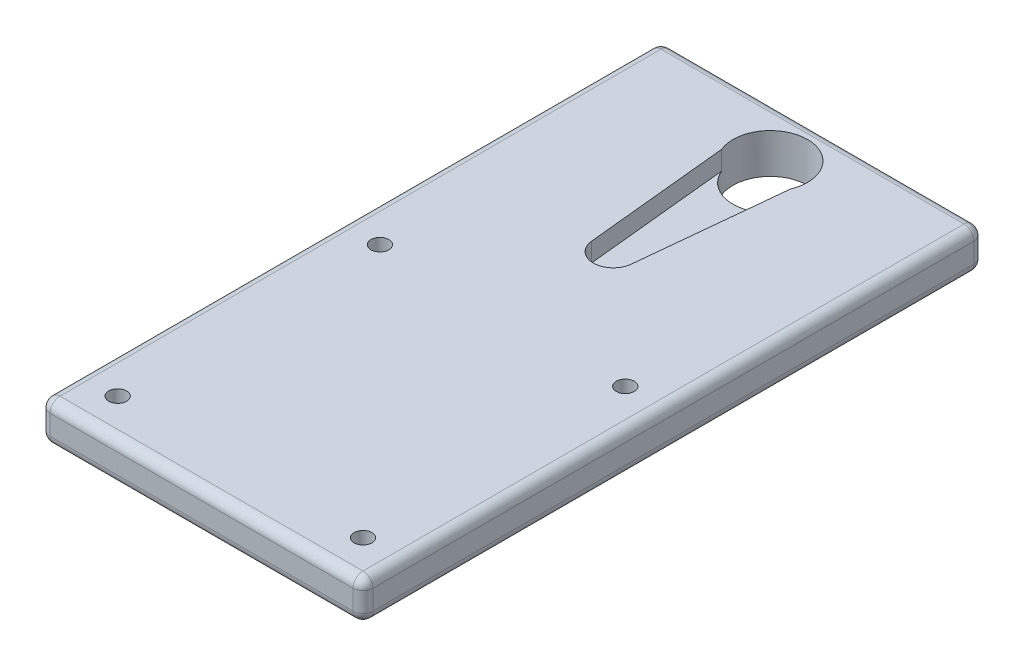
SolidWorks part; units mm, degrees
ref_plane "Front Plane" through (0, 0, 0) normal (0, 0, 1) x (1, 0, 0)
ref_plane "Top Plane" through (0, 0, 0) normal (0, 1, 0) x (1, 0, 0)
ref_plane "Right Plane" through (0, 0, 0) normal (1, 0, 0) x (0, 0, -1)
sketch "Sketch1" plane through (0, 0, 0) normal (0, 1, 0) x (1, 0, 0)
  line L1 (-16.25, 62.5) -> (16.25, 62.5)
  line L2 (-16.25, 62.5) -> (-16.25, 0)
  line L3 (-16.25, 0) -> (16.25, 0)
  line L4 (16.25, 62.5) -> (16.25, 0)
  point P4 (0, 0)
  dimension "D1" = 32.5
  dimension "D2" = 62.5
extrude "Base" add sketch "Sketch1" along normal blind 4
sketch "Sketch2" plane through (0, 4, 0) normal (0, 1, 0) x (1, 0, 0)
  line L0 (-3.4645, 55.8149) -> (-2, 41.25)
  line L1 (3.4645, 55.8149) -> (2, 41.25)
  line L2 (0, 62.5) -> (0, 0) construction
  line L3 (16.25, 62.5) -> (-16.25, 62.5) construction
  line L4 (-16.25, 0) -> (16.25, 0) construction
  arc A0 (-2, 41.25) -> (2, 41.25) centre (0, 41.4511) ccw
  arc A1 (-3.4645, 55.8149) -> (3.4645, 55.8149) centre (0, 57.25) cw
  point P11 (0, 39.441)
  point P13 (0, 61)
  point P14 (0, 0)
  dimension "D1" = 2.0101
  dimension "D4" = 3.75
  dimension "D2" = 14.5649
  dimension "D3" = 5.742
  dimension "D5" = 1.5
extrude "Servo Arm Slot" cut sketch "Sketch2" against normal blind 1.9
sketch "Sketch3" plane through (0, 2.1, 0) normal (0, 1, 0) x (1, 0, 0)
  circle A0 centre (0, 57.25) radius 3.75
  arc A1 (3.4645, 55.8149) -> (-3.4645, 55.8149) centre (0, 57.25) ccw construction
  dimension "D1" = 7.5
extrude "Servo Arm Mounting Hole" cut sketch "Sketch3" against normal through all
sketch "Sketch4" plane through (0, 0, 0) normal (0, -1, 0) x (1, 0, 0)
  line L0 (-12.35, 0) -> (-12.35, -62.5) construction
  line L1 (-16.25, 0) -> (16.25, 0) construction
  line L2 (16.25, -62.5) -> (-16.25, -62.5) construction
  line L3 (-16.25, -62.5) -> (-16.25, 0) construction
  line L4 (0, 0) -> (0, -62.5) construction
  circle A0 centre (-12.35, -3.9) radius 0.9
  circle A1 centre (-12.35, -30.3) radius 0.9
  circle A2 centre (12.35, -30.3) radius 0.9
  circle A3 centre (12.35, -3.9) radius 0.9
  dimension "D2" = 26.4
  dimension "D3" = 3.9
  dimension "D4" = 1.8
  dimension "D1" = 3.9
extrude "Scanner Mounting Holes" cut sketch "Sketch4" against normal through all
chamfer "Mounting Hole Chamfers" distance 1 angle 45 4 edges at (12.35, 0, -29.4) (-12.35, 0, -31.2) (12.35, 0, -3) (-12.35, 0, -4.8)
fillet "Fillet1" radius 1 12 edges at (0, 0, 0) (16.25, 0, -31.25) (0, 0, -62.5) (-16.25, 0, -31.25) (0, 4, 0) (16.25, 4, -31.25) (0, 4, -62.5) (-16.25, 4, -31.25) (16.25, 2, 0) (-16.25, 2, 0) (-16.25, 2, -62.5) (16.25, 2, -62.5)
